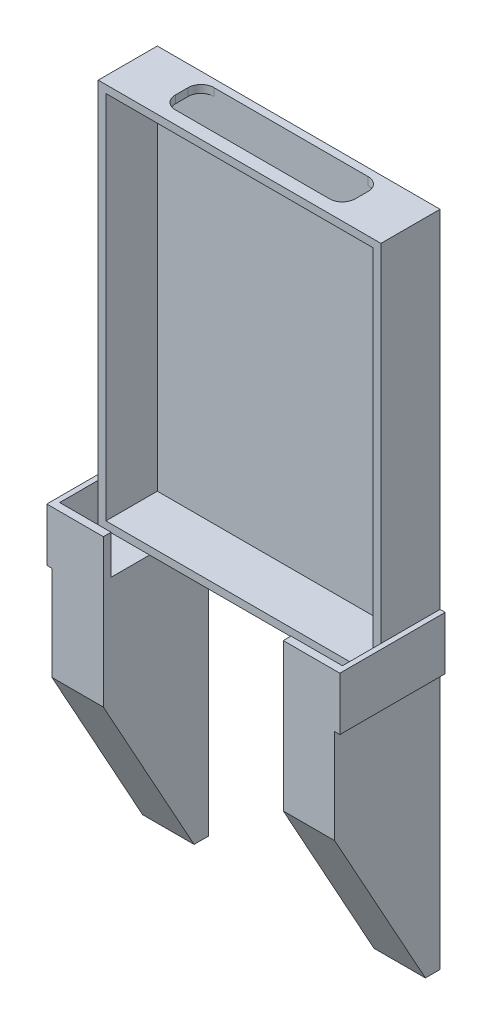
SolidWorks part; units mm, degrees
ref_plane "前视基准面" through (0, 0, 0) normal (0, 0, 1) x (1, 0, 0)
ref_plane "上视基准面" through (0, 0, 0) normal (0, 1, 0) x (1, 0, 0)
ref_plane "右视基准面" through (0, 0, 0) normal (1, 0, 0) x (0, 0, -1)
other "Configuration Table"
sketch "草图1" plane through (0, 0, 0) normal (0, 0, 1) x (1, 0, 0)
  line L1 (-55, -75) -> (55, -75)
  line L2 (-55, -75) -> (-55, 75)
  line L3 (-55, 75) -> (55, 75)
  line L4 (55, -75) -> (55, 75)
  line L5 (-55, -75) -> (55, 75) construction
  line L6 (-55, 75) -> (55, -75) construction
  point P0 (0, 0)
  dimension "D1" = 110
  dimension "D2" = 150
extrude "凸台-拉伸1" add sketch "草图1" along normal blind 3
sketch "草图2" plane through (0, 0, 3) normal (0, 0, 1) x (1, 0, 0)
  line L0 (52, -72) -> (52, 72)
  line L1 (52, 72) -> (-52, 72)
  line L2 (-52, 72) -> (-52, -72)
  line L3 (-52, -72) -> (52, -72)
  line L4 (55, -75) -> (55, 75)
  line L5 (55, 75) -> (-55, 75)
  line L6 (-55, 75) -> (-55, -75)
  line L7 (-55, -75) -> (55, -75)
  line L8 (55, -75) -> (55, 75)
  line L9 (55, 75) -> (-55, 75)
  line L10 (-55, 75) -> (-55, -75)
  line L11 (-55, -75) -> (55, -75)
  dimension "D1" = 0
  dimension "D2" = 3
extrude "凸台-拉伸2" add sketch "草图2" along normal blind 20
sketch "草图3" plane through (-55, 0, 0) normal (-1, 0, 0) x (0, 0, 1)
  line L0 (23, -75) -> (38, -75)
  line L1 (38, -75) -> (38, -59.8162)
  line L2 (38, -59.8162) -> (41, -59.8162)
  line L3 (41, -59.8162) -> (41, -117.235)
  line L4 (41, -117.235) -> (5.7002, -181.1638)
  line L5 (5.7002, -181.1638) -> (0, -181.1638)
  line L6 (0, -181.1638) -> (0, -75)
  line L7 (0, -75) -> (23, -75)
  dimension "D1" = 15
  dimension "D2" = 3
extrude "凸台-拉伸3" add sketch "草图3" against normal blind 20
sketch "草图4" plane through (-55, 0, 0) normal (-1, 0, 0) x (0, 0, 1)
  line L0 (0, 75) -> (0, -181.1638) construction
  line L1 (41, -59.8162) -> (0, -59.8162)
  line L2 (41, -59.8162) -> (41, -80.5021)
  line L3 (41, -80.5021) -> (0, -80.5021)
  line L4 (0, -59.8162) -> (0, -80.5021)
extrude "凸台-拉伸4" add sketch "草图4" along normal blind 2
sketch "草图5" plane through (0, 75, 0) normal (0, 1, 0) x (1, 0, 0)
  line L0 (55, 0) -> (-55, 0) construction
  line L1 (-35, -3) -> (35, -3)
  line L2 (-35, -3) -> (-35, -18)
  line L3 (-35, -18) -> (35, -18)
  line L4 (35, -3) -> (35, -18)
  line L5 (55, -23) -> (55, 0) construction
  line L6 (-55, -23) -> (-55, 0) construction
  dimension "D1" = 3
  dimension "D2" = 15
  dimension "D3" = 20
  dimension "D4" = 20
extrude "切除-拉伸1" cut sketch "草图5" against normal blind 8
fillet "圆角1" radius 5 4 edges at (-35, 73.5, 18) (-35, 73.5, 3) (35, 73.5, 18) (35, 73.5, 3)
mirror "镜向1" about plane through (0, 0, 0) normal (1, 0, 0) of "凸台-拉伸4", "凸台-拉伸1"
mirror "镜向2" about plane through (0, 0, 0) normal (1, 0, 0) of "凸台-拉伸3"
